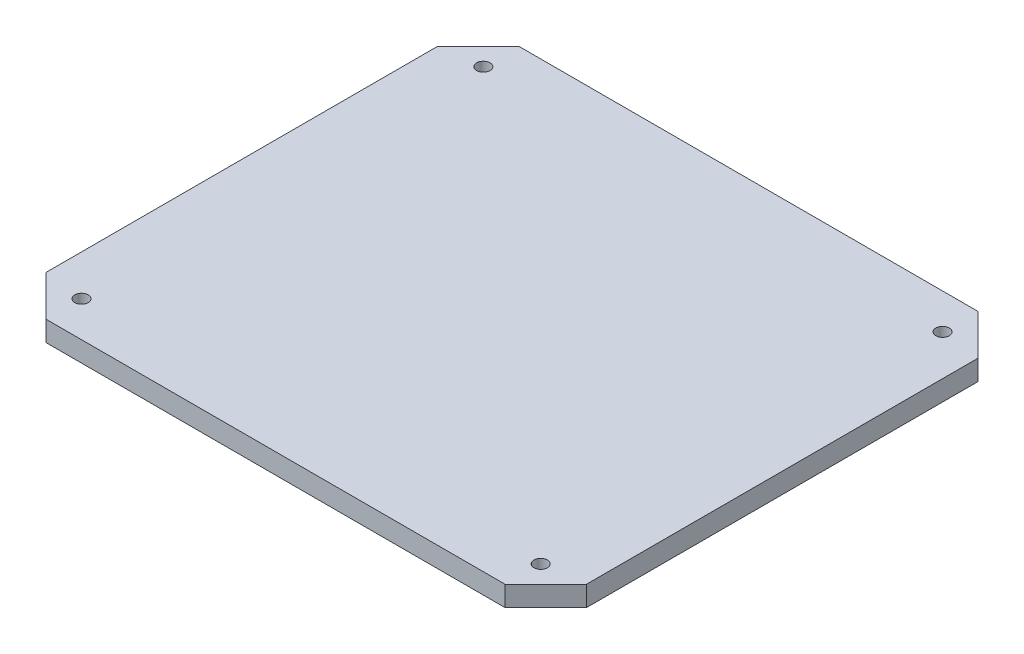
SolidWorks part; units mm, degrees
ref_plane "Front Plane" through (0, 0, 0) normal (0, 0, 1) x (1, 0, 0)
ref_plane "Top Plane" through (0, 0, 0) normal (0, 1, 0) x (1, 0, 0)
ref_plane "Right Plane" through (0, 0, 0) normal (1, 0, 0) x (0, 0, -1)
sketch "Sketch1" plane through (0, 0, 0) normal (0, 1, 0) x (1, 0, 0)
  line L0 (0, 175) -> (0, -175) construction
  line L1 (-200, -175) -> (200, -175)
  line L2 (-200, -175) -> (-200, 175)
  line L3 (-200, 175) -> (200, 175)
  line L4 (200, -175) -> (200, 175)
  line L5 (-200, -175) -> (200, 175) construction
  line L6 (-200, 175) -> (200, -175) construction
  line L7 (-200, 0) -> (200, 0) construction
  circle A0 centre (-170, 148.75) radius 5
  circle A1 centre (170, 148.75) radius 5
  circle A2 centre (170, -148.75) radius 5
  circle A3 centre (-170, -148.75) radius 5
  point P0 (0, 0)
  dimension "D3" = 30
  dimension "D4" = 10
  dimension "D1" = 350
  dimension "D2" = 400
extrude "Boss-Extrude1" add sketch "Sketch1" along normal blind 15
sketch "Sketch2" plane through (0, 15, 0) normal (0, 1, 0) x (1, 0, 0)
  line L0 (-170, 175) -> (-200, 145)
  line L1 (200, 175) -> (-200, 175) construction
  line L2 (-200, 175) -> (-200, -175) construction
  line L3 (-200, 175) -> (-170, 175)
  line L4 (-200, 145) -> (-200, 175)
  line L5 (0, 175) -> (0, -175) construction
  line L6 (-200, -175) -> (200, -175) construction
  line L7 (-200, 0) -> (200, 0) construction
  line L8 (200, -175) -> (200, 175) construction
  line L9 (170, 175) -> (200, 145)
  line L10 (200, 175) -> (170, 175)
  line L11 (200, 145) -> (200, 175)
  line L12 (200, -175) -> (170, -175)
  line L13 (200, -145) -> (200, -175)
  line L14 (170, -175) -> (200, -145)
  line L15 (-170, -175) -> (-200, -145)
  line L16 (-200, -175) -> (-170, -175)
  line L17 (-200, -145) -> (-200, -175)
  dimension "D1" = 30
  dimension "D2" = 30
extrude "Cut-Extrude1" cut sketch "Sketch2" against normal through all
